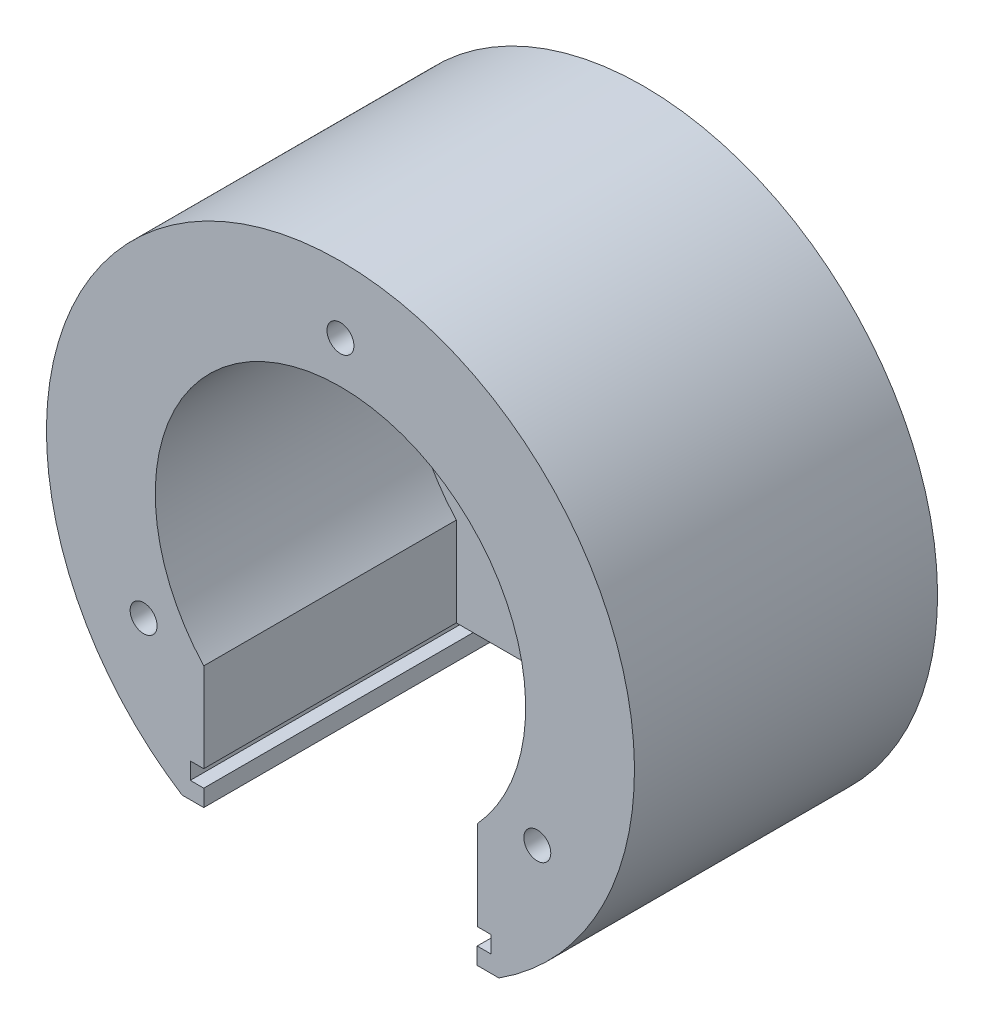
SolidWorks part; units mm, degrees
material "PET"
ref_plane "Front Plane" through (0, 0, 0) normal (0, 0, 1) x (1, 0, 0)
ref_plane "Top Plane" through (0, 0, 0) normal (0, 1, 0) x (1, 0, 0)
ref_plane "Right Plane" through (0, 0, 0) normal (1, 0, 0) x (0, 0, -1)
sketch "Sketch2" plane through (0, 0, 0) normal (0, 0, 1) x (1, 0, 0)
  circle A0 centre (0, 0) radius 17.4625
extrude "Boss-Extrude1" add sketch "Sketch2" along normal blind 18
sketch "Sketch13" plane through (0, 0, 18) normal (0, 0, 1) x (1, 0, 0)
  circle A0 centre (0, 13.5) radius 0.8
  circle A2 centre (11.6913, -6.75) radius 0.8
  circle A3 centre (-11.6913, -6.75) radius 0.8
  point P9 (0, 0)
  dimension "D1" = 3
  dimension "D2" = 13.5
extrude "Cut-Extrude6" cut sketch "Sketch13" against normal blind 7.3
sketch "Sketch16" plane through (0, 0, 18) normal (0, 0, 1) x (1, 0, 0)
  circle A0 centre (0, 0) radius 11
extrude "Cut-Extrude9" cut sketch "Sketch16" against normal blind 15
sketch "Sketch20" plane through (5.9573, 0, -11.0843) normal (0, 1, 0) x (0, 0, 1)
  line L0 (16.5293, -11.0218) -> (16.5293, -6.9068)
  line L1 (23.6393, -11.0218) -> (23.6393, -0.8118)
  line L2 (14.9293, -6.9068) -> (14.9293, -4.9268)
  line L3 (14.9293, -6.9068) -> (16.5293, -6.9068)
  line L4 (14.9293, -4.9268) -> (16.5293, -4.9268)
  line L5 (16.5293, -4.9268) -> (16.5293, -0.8118)
  line L6 (16.5293, -0.8118) -> (18.0543, -0.8118)
  line L7 (18.0543, -0.8118) -> (18.0543, 1.0282)
  line L8 (22.1143, -0.8118) -> (22.1143, 1.0282)
  line L9 (18.0543, 1.0282) -> (22.1143, 1.0282)
  line L10 (18.0543, -12.8618) -> (18.0543, -11.0218)
  line L11 (18.0543, -12.8618) -> (22.1143, -12.8618)
  line L12 (22.1143, -12.8618) -> (22.1143, -11.0218)
  line L13 (23.6393, -0.8118) -> (22.1143, -0.8118)
  line L14 (23.6393, -11.0218) -> (22.1143, -11.0218)
  line L15 (16.5293, -11.0218) -> (18.0543, -11.0218)
  line L16 (29.0843, -9.7935) -> (23.6393, -9.7935) construction
  line L18 (29.0843, -23.4198) -> (29.0843, 11.5052) construction
  line L19 (16.5293, -9.7935) -> (11.0843, -9.7935) construction
  line L20 (11.0843, 11.5052) -> (11.0843, -23.4198) construction
  dimension "D2" = 4.06
  dimension "D3" = 10.21
  dimension "D4" = 13.89
  dimension "D5" = 1.98
  dimension "D6" = 8.71
  dimension "D7" = 7.11
extrude "Cut-Extrude11" cut sketch "Sketch20" against normal blind 22
sketch "Sketch21" plane through (0, 0, 18) normal (0, 0, 1) x (1, 0, 0)
  line L1 (-8.125, -15.46) -> (8.125, -15.46)
  line L2 (-8.125, -15.46) -> (-8.125, -18.2444)
  line L3 (-8.125, -18.2444) -> (8.125, -18.2444)
  line L4 (8.125, -15.46) -> (8.125, -18.2444)
  dimension "D1" = 16.25
  dimension "D2" = 8.125
  dimension "D3" = 15.46
extrude "Cut-Extrude12" cut sketch "Sketch21" against normal through all
sketch "Sketch24" plane through (0, 0, 18) normal (0, 0, 1) x (1, 0, 0)
  line L0 (-8.1196, -6.7586) -> (8.1304, -6.7586)
  line L1 (-8.1196, -6.7586) -> (-8.1196, -13.46)
  line L2 (-8.1196, -13.46) -> (8.1304, -13.46)
  line L3 (8.1304, -6.7586) -> (8.1304, -13.46)
  dimension "D1" = 16.25
extrude "Cut-Extrude13" cut sketch "Sketch24" against normal up to surface (15 mm away) up to face at (11, 0, 3)
sketch "Sketch26" plane through (0, 0, 18) normal (0, 0, 1) x (1, 0, 0)
  line L4 (-8.1196, -13.71) -> (-8.1196, -15.46)
  line L5 (-8.1196, -15.46) -> (8.1196, -15.46)
  line L6 (8.1196, -15.46) -> (8.1196, -13.71)
  line L14 (-8.9196, -13.71) -> (-8.1196, -13.71)
  line L17 (8.9304, -13.71) -> (8.1196, -13.71)
  line L18 (-8.9196, -13.71) -> (-8.9196, -12.71)
  line L19 (-8.9196, -12.71) -> (8.9304, -12.71)
  line L20 (8.9304, -12.71) -> (8.9304, -13.71)
  dimension "D1" = 1
  dimension "D2" = 1
  dimension "D3" = 1.75
extrude "Cut-Extrude14" cut sketch "Sketch26" against normal blind 17
sketch "Sketch27" plane through (0, 0, 18) normal (0, 0, 1) x (1, 0, 0)
  line L0 (-8.1196, -15.46) -> (8.1196, -15.46) construction
  line L1 (-9.4104, -14.71) -> (9.4104, -14.71)
  line L2 (-9.4104, -14.71) -> (-9.4104, -15.46)
  line L3 (-9.4104, -15.46) -> (9.4104, -15.46)
  line L4 (9.4104, -14.71) -> (9.4104, -15.46)
  arc A0 (8.1196, -15.46) -> (-8.1196, -15.46) centre (0, 0) ccw construction
  point P9 (9.3727, -14.734)
  dimension "D2" = 0.75
extrude "Cut-Extrude15" cut sketch "Sketch27" against normal through all
